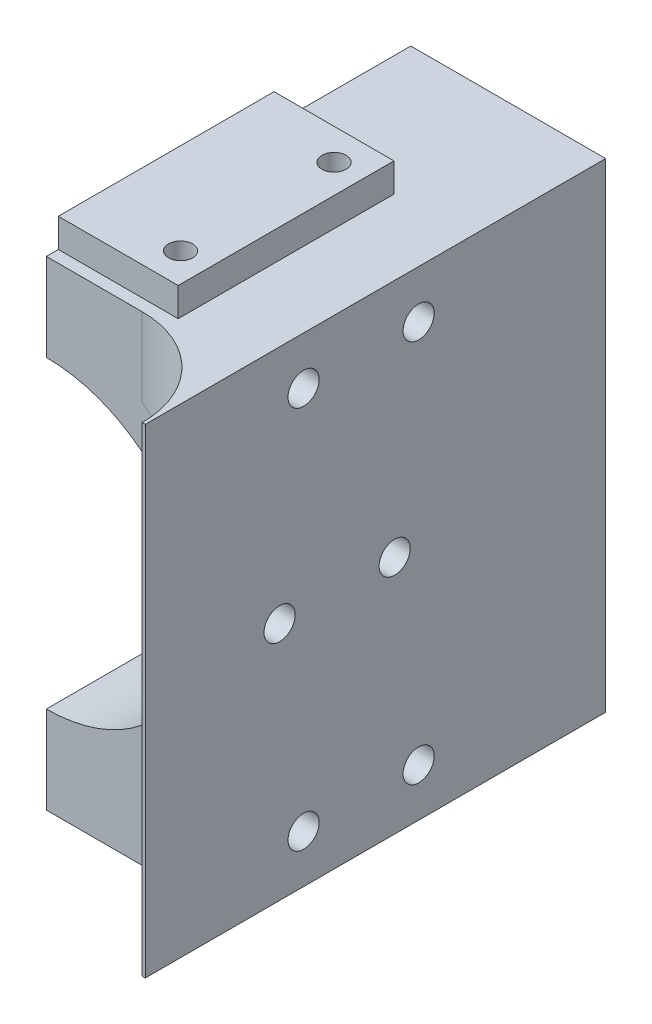
SolidWorks part; units mm, degrees
other "Markup1"
sketch "Sketch12" plane through (-50, 56, -10) normal (-0.1438, 0.9756, -0.1662) x (-0.9889, -0.1353, 0.0611)
material "6061-T6 (SS)"
ref_plane "Front Plane" through (0, 0, 0) normal (0, 0, 1) x (1, 0, 0)
ref_plane "Top Plane" through (0, 0, 0) normal (0, 1, 0) x (1, 0, 0)
ref_plane "Right Plane" through (0, 0, 0) normal (1, 0, 0) x (0, 0, -1)
sketch "Sketch1" plane through (0, 0, 0) normal (0, 0, 1) x (1, 0, 0)
  circle A2 centre (0, 0) radius 31.75
  circle A4 centre (0, 0) radius 39.1
  circle A5 centre (0, 0) radius 38.1 construction
  dimension "D1" = 1
  dimension "D2" = 63.5
extrude "Centre Hole for L2" add sketch "Sketch1" along normal blind 40 and the other way blind 10 contours A4 | A2
sketch "Sketch2" plane through (0, 0, 40) normal (0, 0, 1) x (1, 0, 0)
  line L0 (0, 48.4974) -> (0, 0) construction
  line L5 (-50, 50) -> (-50, -50)
  line L12 (0, 0) -> (72.986, 0) construction
  line L16 (-50, 50) -> (50, 50)
  line L17 (50, 50) -> (50, -50)
  line L18 (-50, -50) -> (50, -50)
  circle A2 centre (0, 0) radius 39.1
  circle A3 centre (0, 0) radius 39.1 construction
  point P13 (0, 50)
  dimension "D1" = 50
  dimension "D2" = 100
extrude "Main Structure" add sketch "Sketch2" along normal blind 60 and the other way blind 50 contours L5 L18 L17 L16 A2
sketch "Sketch3" plane through (-50, 0, 0) normal (-1, 0, 0) x (0, 0, 1)
  line L0 (100, 50) -> (100, -50) construction
  line L1 (100, 50) -> (100, -50)
  line L2 (-10, 50) -> (100, 50) construction
  line L3 (-10, -50) -> (100, -50) construction
  line L4 (-10, 50) -> (100, 50) construction
  arc A0 (100, 50) -> (100, -50) centre (100, 0) cw
extrude "Bearing Curve" add sketch "Sketch3" against normal blind 10 contours A0 L1
mirror "Upright Mirror" about plane through (0, 0, 0) normal (1, 0, 0) of "Bearing Curve"
sketch "Sketch6" plane through (-50, 0, 0) normal (-1, 0, 0) x (0, 0, 1)
  circle A0 centre (100, 0) radius 10.5
  dimension "D1" = 21
extrude "Shaft Hole" cut sketch "Sketch6" against normal up to surface (10 mm away) up to face at (-40, 0, 125)
sketch "Sketch4" plane through (0, 50, 0) normal (0, 1, 0) x (1, 0, 0)
  line L0 (0, -100) -> (0, 10) construction
  line L3 (-40, -100) -> (-40, -60)
  line L6 (40, -100) -> (40, -60)
  line L7 (-50, 10) -> (50, 10) construction
  line L8 (-40, -100) -> (40, -100) construction
  line L9 (-20, -40) -> (20, -40)
  line L10 (-40, -100) -> (40, -100)
  arc A0 (-40, -60) -> (-20, -40) centre (-20, -60) cw
  arc A1 (40, -60) -> (20, -40) centre (20, -60) ccw
  point P17 (0, -100)
  dimension "D2" = 20
  dimension "D1" = 50
extrude "Wrist Cutout" cut sketch "Sketch4" against normal through all
ref_plane "Plane1" through (0, 0, 0) normal (-1, 0, 0) x (0, 0, 1)
other "SurfaceCut1"
sketch "Sketch11" plane through (0, 50, 0) normal (0, 1, 0) x (1, 0, 0)
  line L0 (0, -40) -> (0, 10) construction
  line L1 (0, -37.5) -> (-25, -37.5)
  line L2 (0, -37.5) -> (0, 7.5)
  line L3 (0, 7.5) -> (-25, 7.5)
  line L4 (-25, -37.5) -> (-25, 7.5)
  line L5 (-50, 10) -> (0, 10) construction
  circle A0 centre (-19, 1) radius 2.525
  circle A1 centre (-19, -31) radius 2.525
  dimension "D4" = 5.05
  dimension "D5" = 19
  dimension "D6" = 6.5
  dimension "D7" = 5.05
  dimension "D8" = 19
  dimension "D1" = 45
  dimension "D2" = 25
  dimension "D3" = 2.5
  dimension "6.5" = 6.5
extrude "Boss-Extrude1" add sketch "Sketch11" along normal blind 6
sketch "Sketch15" plane through (0, -50, 0) normal (0, -1, 0) x (-1, 0, 0)
  line L1 (0, -40) -> (19.8, -40)
  line L2 (0, -40) -> (0, -33)
  line L3 (0, -33) -> (19.8, -33)
  line L4 (19.8, -40) -> (19.8, -33)
  dimension "D1" = 19.8
  dimension "D2" = 7
extrude "Cut-Extrude4" [suppressed] cut sketch "Sketch15" against normal blind 4
sketch "Sketch16" [suppressed] plane through (0, -46, 0) normal (0, -1, 0) x (-1, 0, 0)
  line L0 (19.8, -40) -> (19.8, -33) construction
  line L1 (19.8, -33) -> (0, -33) construction
  line L2 (14.65, -35.9) -> (4.8172, -35.9) construction
  circle A0 centre (14.65, -35.9) radius 1.5
  circle A1 centre (5.15, -35.9) radius 1.5
  point P4 (19.8, -36.5)
  dimension "D1" = 3
  dimension "D2" = 5.15
  dimension "D3" = 2.9
  dimension "D4" = 3
  dimension "D5" = 9.5
extrude "Cut-Extrude5" [suppressed] cut sketch "Sketch16" against normal up to surface (17.8319 mm away)
sketch "Sketch18" plane through (-50, 0, 0) normal (-1, 0, 0) x (0, 0, 1)
  line L2 (-10, 50) -> (-10, -50) construction
  line L4 (-10, 50) -> (100, 50) construction
  circle A0 centre (8, 0) radius 3.25
  circle A1 centre (32, 0) radius 3.25
  dimension "D1" = 6.5
  dimension "D2" = 6.5
  dimension "D3" = 18
  dimension "D4" = 50
  dimension "D6" = 24
extrude "Cut-Extrude6" cut sketch "Sketch18" against normal through all and the other way through all
sketch "Sketch19" plane through (-40, 0, 0) normal (1, 0, 0) x (0, 0, -1)
  line L3 (-60, 50) -> (-100, 50)
  line L4 (-100, -50) -> (-60, -50)
  line L5 (-60, -50) -> (-60, 50)
  line L6 (-60, 50) -> (-100, 50)
  line L7 (-100, -50) -> (-60, -50)
  line L8 (-60, -50) -> (-60, 50)
  arc A1 (-100, 50) -> (-100, -50) centre (-100, 0) ccw
  arc A2 (-100, 50) -> (-100, -50) centre (-100, 0) ccw
  dimension "D1" = 0
extrude "Cut-Extrude7" cut sketch "Sketch19" against normal blind 1.5875
sketch "Sketch9" plane through (-41.5875, 0, 0) normal (1, 0, 0) x (0, 0, -1)
  circle A0 centre (-100, 0) radius 12.05
  dimension "D1" = 24.1
extrude "Bearing" cut sketch "Sketch9" against normal blind 5
sketch "Sketch20" plane through (-50, 0, 0) normal (-1, 0, 0) x (0, 0, 1)
  line L3 (-10, -50) -> (100, -50)
  line L4 (100, 50) -> (-10, 50)
  line L5 (-10, 50) -> (-10, -50)
  line L6 (-10, -50) -> (100, -50)
  line L7 (100, 50) -> (-10, 50)
  line L8 (-10, 50) -> (-10, -50)
  arc A1 (100, -50) -> (100, 50) centre (100, 0) ccw
  arc A2 (100, -50) -> (100, 50) centre (100, 0) ccw
  dimension "D1" = 0
extrude "Cut-Extrude8" cut sketch "Sketch20" against normal blind 3
sketch "Sketch21" plane through (-47, 0, 0) normal (-1, 0, 0) x (0, 0, 1)
  line L0 (3, -40) -> (27, -40) construction
  line L1 (8, 0) -> (8, -40) construction
  line L2 (100, 0) -> (-10, 0) construction
  line L3 (-10, 50) -> (-10, -50) construction
  line L4 (100, 0) -> (150, 0) construction
  circle A2 centre (3, -40) radius 3.25
  circle A3 centre (27, -40) radius 3.25
  circle A4 centre (27, 40) radius 3.25
  circle A5 centre (3, 40) radius 3.25
  arc A6 (100, -50) -> (100, 50) centre (100, 0) ccw construction
  circle A7 centre (125, 0) radius 1.65
  circle A8 centre (32, 0) radius 3.25 construction
  dimension "D1" = 6.5
  dimension "D5" = 3.3
  dimension "D2" = 40
  dimension "D3" = 5
  dimension "D4" = 5
extrude "Cut-Extrude9" cut sketch "Sketch21" against normal through all
sketch "Sketch22" plane through (-47, 0, 0) normal (-1, 0, 0) x (0, 0, 1)
  line L3 (-10, 50) -> (-10, -50)
  line L4 (-10, -50) -> (100, -50)
  line L5 (100, 50) -> (-10, 50)
  line L6 (-10, 50) -> (-10, -50)
  line L7 (-10, -50) -> (100, -50)
  line L8 (100, 50) -> (-10, 50)
  arc A1 (100, -50) -> (100, 50) centre (100, 0) ccw
  arc A2 (100, -50) -> (100, 50) centre (100, 0) ccw
  dimension "D1" = 0
extrude "Cut-Extrude10" cut sketch "Sketch22" against normal blind 6.35
sketch "Sketch23" plane through (0, -50, 0) normal (0, -1, 0) x (-1, 0, 0)
  line L0 (0, -40) -> (0, 10) construction
  line L5 (40.65, 0.25) -> (0, 0.25) construction
  circle A0 centre (15, 3.25) radius 2.275
  dimension "D1" = 4.55
  dimension "D2" = 15
  dimension "D3" = 3
extrude "Cut-Extrude11" cut sketch "Sketch23" against normal blind 6
chamfer "Chamfer1" distance 0.5 angle 45 1 edges at (-15, -50, -5.525)
mirror "Mirror1" about plane through (0, 0, 0) normal (-1, 0, 0) of bodies 150
delete or keep bodies "Body-Delete/Keep 1" type delete bodies bodies 150
sketch "Sketch24" plane through (0, 0, -10) normal (0, 0, -1) x (-1, 0, 0)
  line L5 (-40.65, 50) -> (-40.65, -50)
  line L6 (-40.65, -50) -> (0, -50)
  line L7 (0, -50) -> (0, -31.75)
  line L8 (0, 31.75) -> (0, 50)
  line L9 (0, 50) -> (-40.65, 50)
  line L10 (-40.65, 50) -> (-40.65, -50)
  line L11 (-40.65, -50) -> (0, -50)
  line L12 (0, -50) -> (0, -31.75)
  line L13 (0, 31.75) -> (0, 50)
  line L14 (0, 50) -> (-40.65, 50)
  arc A1 (0, 31.75) -> (0, -31.75) centre (0, 0) ccw
  arc A2 (0, 31.75) -> (0, -31.75) centre (0, 0) ccw
  dimension "D1" = 0
extrude "Boss-Extrude2" add sketch "Sketch24" along normal blind 26
